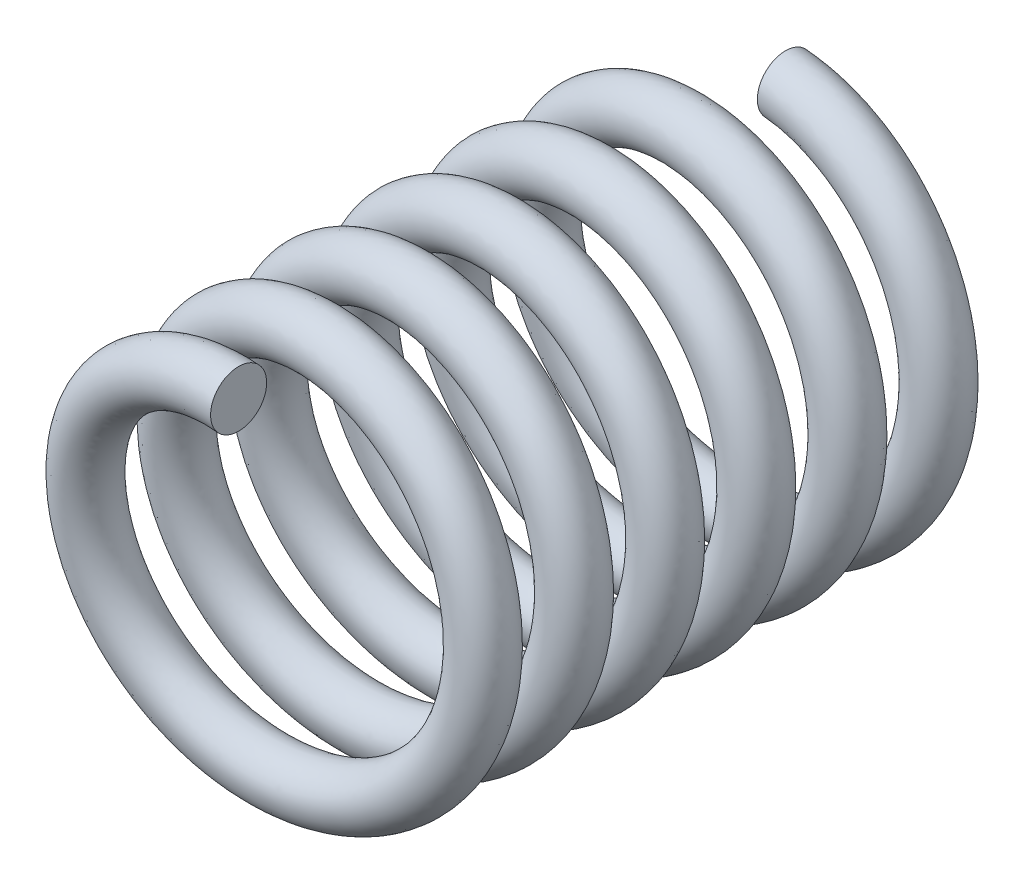
SolidWorks part; units mm, degrees
material "Cast Alloy Steel"
ref_plane "Front Plane" through (0, 0, 0) normal (0, 0, 1) x (1, 0, 0)
ref_plane "Top Plane" through (0, 0, 0) normal (0, 1, 0) x (1, 0, 0)
ref_plane "Right Plane" through (0, 0, 0) normal (1, 0, 0) x (0, 0, -1)
sketch "Base Sketch" plane through (0, 0, 0) normal (0, 0, 1) x (1, 0, 0)
  circle A0 centre (0, 0) radius 15.875
  dimension "D1" = 31.75
curve "Helix Base" pitch 8.255 height 49.53 turns 6
sketch "Coil Sketch" plane through (0, 0, 0) normal (1, 0, 0) x (0, 0, -1)
  circle A0 centre (0, 15.875) radius 2.54
  point P2 (0, 0)
  point P3 (0, 0)
  point P4 (0, 0)
  dimension "D1" = 5.08
sweep "Coil Sweep" add profiles "Coil Sketch" path "Helix Base"
